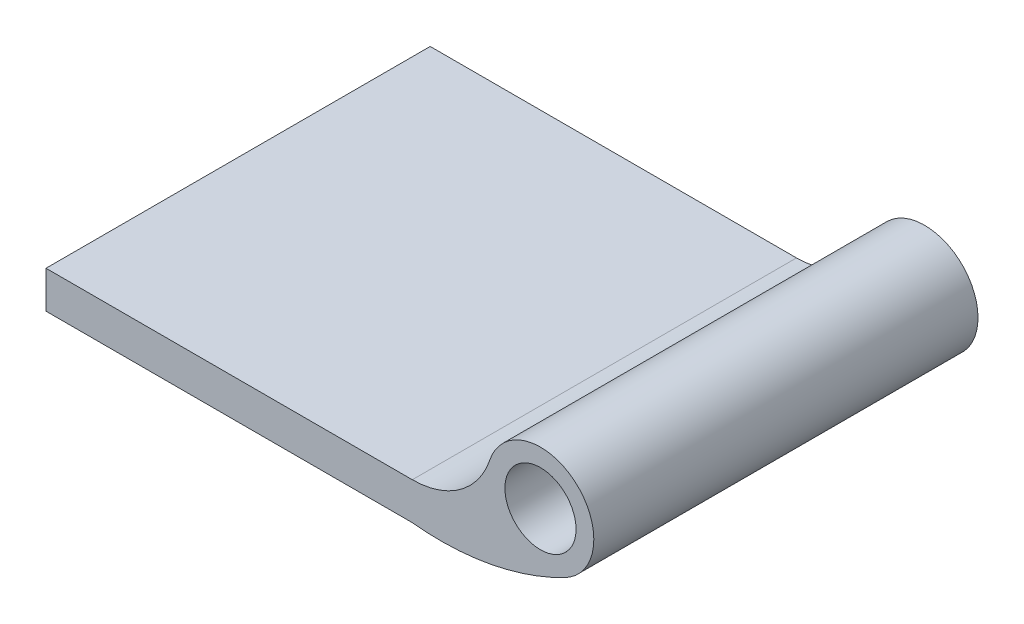
SolidWorks part; units mm, degrees
material "1023 Carbon Steel Sheet (SS)"
ref_plane "Front Plane" through (0, 0, 0) normal (0, 0, 1) x (1, 0, 0)
ref_plane "Top Plane" through (0, 0, 0) normal (0, 1, 0) x (1, 0, 0)
ref_plane "Right Plane" through (0, 0, 0) normal (1, 0, 0) x (0, 0, -1)
sketch "Sketch1" plane through (0, 0, 0) normal (0, 0, 1) x (1, 0, 0)
  line L0 (-139, -21.4208) -> (-36.0263, -21.4208)
  line L1 (-139, -21.4208) -> (-139, -10.9628)
  line L2 (-139, -10.9628) -> (-36.0263, -10.9628)
  line L3 (-36.0263, -21.4208) -> (-36.0263, -10.9628)
  line L4 (15, 28.3476) -> (15, -45.7299) construction
  circle A0 centre (0, 0) radius 10
  circle A1 centre (0, 0) radius 15
  arc A2 (6.9149, -13.3111) -> (-36.0263, -21.4208) centre (-28.023, 53.9438) cw
  arc A3 (-14.2296, 4.7452) -> (-36.0263, -10.9628) centre (-36.0263, 12.0139) cw
  dimension "D1" = 20
  dimension "D2" = 30
  dimension "D3" = 154
extrude "Boss-Extrude1" add sketch "Sketch1" along normal blind 108 contours L0 L3 L2 L1 | A1 A3 L3 A2 | A1 A0
